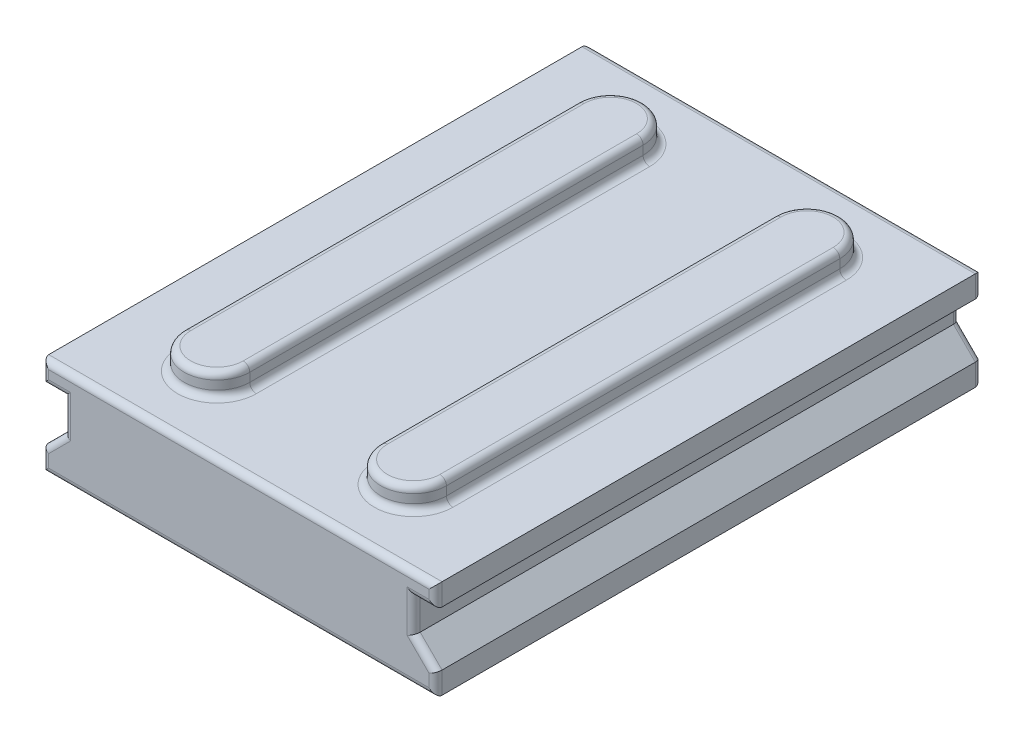
SolidWorks part; units mm, degrees
ref_plane "Front Plane" through (0, 0, 0) normal (0, 0, 1) x (1, 0, 0)
ref_plane "Top Plane" through (0, 0, 0) normal (0, 1, 0) x (1, 0, 0)
ref_plane "Right Plane" through (0, 0, 0) normal (1, 0, 0) x (0, 0, -1)
sketch "Sketch1" plane through (0, 0, 0) normal (0, 0, 1) x (1, 0, 0)
  line L12 (8, -1) -> (8, -2.5)
  line L13 (8, -2.5) -> (9, -3.5)
  line L14 (9, -3.5) -> (9, -4.5)
  line L15 (9, -4.5) -> (-9, -4.5)
  line L16 (0, 0) -> (0, -4.5) construction
  line L17 (-9, -3.5) -> (-9, -4.5)
  line L18 (-8, -2.5) -> (-9, -3.5)
  line L19 (-8, -1) -> (-8, -2.5)
  line L21 (9, -1) -> (9, 0)
  line L22 (9, 0) -> (-9, 0)
  line L24 (8, -1) -> (9, -1)
  line L25 (-8, -1) -> (-9, -1)
  line L26 (-9, -1) -> (-9, 0)
  point P20 (0, 0)
  dimension "D1" = 8
  dimension "D2" = 1.5
  dimension "D3" = 1
  dimension "D4" = 135
  dimension "D5" = 18
  dimension "D6" = 1
extrude "Boss-Extrude1" add sketch "Sketch1" along normal blind 25
sketch "Sketch2" plane through (0, 0, 0) normal (0, 1, 0) x (1, 0, 0)
  line L0 (0, 0) -> (0, -25) construction
  line L2 (4.5, 0) -> (4.5, -25) construction
  line L4 (4.5, -3.5) -> (4.5, -21.5) construction
  line L5 (6, -3.5) -> (6, -21.5)
  line L6 (3, -3.5) -> (3, -21.5)
  line L7 (0, 0) -> (9, 0) construction
  line L8 (-4.5, -3.5) -> (-4.5, -21.5) construction
  line L9 (-6, -3.5) -> (-6, -21.5)
  line L10 (-3, -3.5) -> (-3, -21.5)
  line L11 (9, -25) -> (-9, -25) construction
  arc A0 (6, -3.5) -> (3, -3.5) centre (4.5, -3.5) ccw
  arc A1 (3, -21.5) -> (6, -21.5) centre (4.5, -21.5) ccw
  arc A2 (-6, -3.5) -> (-3, -3.5) centre (-4.5, -3.5) cw
  arc A3 (-3, -21.5) -> (-6, -21.5) centre (-4.5, -21.5) cw
  point P11 (4.5, -12.5)
  point P22 (-4.5, -12.5)
  dimension "D1" = 3
  dimension "D2" = 18
extrude "Boss-Extrude2" add sketch "Sketch2" along normal blind 1
fillet "Fillet1" radius 0.3 16 edges at (-6, 1, 12.5) (-4.5, 1, 2) (-3, 1, 12.5) (4.5, 1, 23) (3, 1, 12.5) (4.5, 1, 2) (-4.5, 1, 23) (6, 1, 12.5) (-4.5, 0, 23) (-6, 0, 12.5) (-4.5, 0, 2) (4.5, 0, 23) (3, 0, 12.5) (4.5, 0, 2) (-3, 0, 12.5) (6, 0, 12.5)
fillet "Fillet2" radius 0.3 24 edges at (-8, -1.75, 0) (-8.5, -3, 0) (-9, -4, 0) (0, -4.5, 0) (9, -4, 0) (8.5, -3, 0) (8, -1.75, 0) (-8, -1.75, 25) (-8.5, -3, 25) (-9, -4, 25) (0, -4.5, 25) (9, -4, 25) (8.5, -3, 25) (8, -1.75, 25) (-8.5, -1, 0) (-9, -0.5, 0) (0, 0, 0) (9, -0.5, 0) (8.5, -1, 0) (-9, -0.5, 25) (-8.5, -1, 25) (0, 0, 25) (9, -0.5, 25) (8.5, -1, 25)
